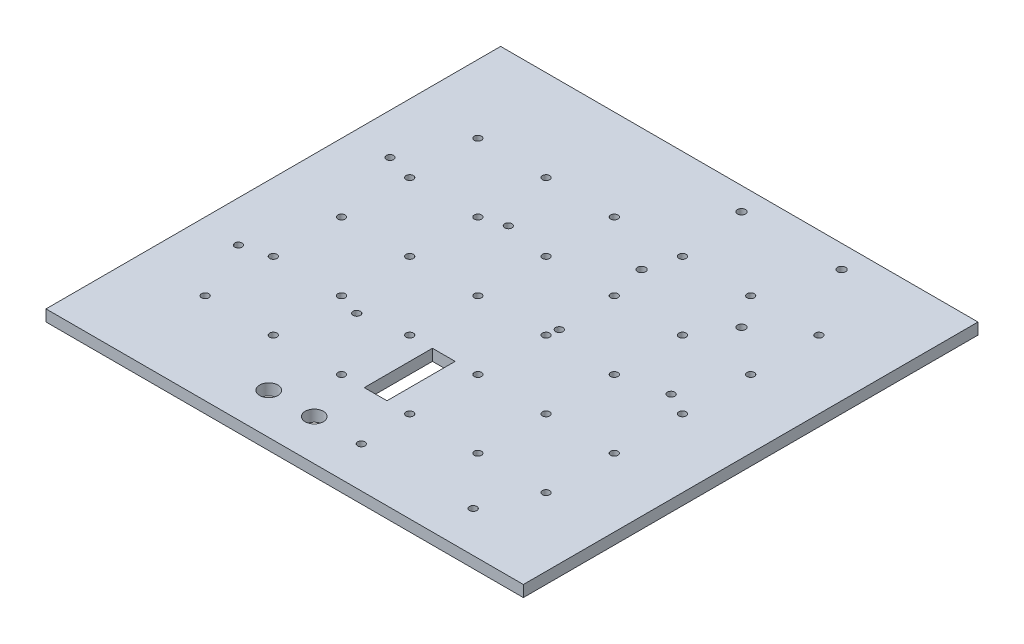
SolidWorks part; units mm, degrees
ref_plane "前视基准面" through (0, 0, 0) normal (0, 0, 1) x (1, 0, 0)
ref_plane "上视基准面" through (0, 0, 0) normal (0, 1, 0) x (1, 0, 0)
ref_plane "右视基准面" through (0, 0, 0) normal (1, 0, 0) x (0, 0, -1)
other "Configuration Table"
sketch "草图1" plane through (0, 0, 0) normal (0, 1, 0) x (1, 0, 0)
  line L4 (105.7144, 99.2856) -> (-104.2856, 99.2856)
  line L5 (-104.2856, 99.2856) -> (-104.2856, -100.7144)
  line L6 (-104.2856, -100.7144) -> (105.7144, -100.7144)
  line L7 (105.7144, -100.7144) -> (105.7144, 99.2856)
  circle A0 centre (-74.2856, -60.7144) radius 1.6
  circle A1 centre (75.7144, 59.2856) radius 1.6
  circle A2 centre (-74.2856, 29.2856) radius 1.6
  circle A3 centre (-74.2856, -0.7144) radius 1.6
  circle A4 centre (-74.2856, -30.7144) radius 1.6
  circle A5 centre (-44.2856, -60.7144) radius 1.6
  circle A6 centre (-44.2856, 59.2856) radius 1.6
  circle A7 centre (45.7144, 59.2856) radius 1.6
  circle A8 centre (75.7144, -30.7144) radius 1.6
  circle A9 centre (75.7144, -0.7144) radius 1.6
  circle A10 centre (45.7144, -60.7144) radius 1.6
  circle A11 centre (75.7144, 29.2856) radius 1.6
  circle A12 centre (75.7144, -60.7144) radius 1.6
  circle A13 centre (-74.2856, 59.2856) radius 1.6
  circle A14 centre (-44.2856, 29.2856) radius 1.6
  circle A15 centre (-44.2856, -0.7144) radius 1.6
  circle A16 centre (-44.2856, -30.7144) radius 1.6
  circle A17 centre (-14.2856, 59.2856) radius 1.6
  circle A21 centre (-14.2856, -60.7144) radius 1.6
  circle A22 centre (15.7144, 59.2856) radius 1.6
  circle A26 centre (15.7144, -60.7144) radius 1.6
  circle A27 centre (45.7144, 59.2856) radius 1.6
  circle A28 centre (45.7144, 29.2856) radius 1.6
  circle A29 centre (45.7144, -0.7144) radius 1.6
  circle A30 centre (45.7144, -30.7144) radius 1.6
  circle A31 centre (45.7144, -60.7144) radius 1.6
  circle A32 centre (15.7144, 29.2856) radius 1.6 [skipped]
  circle A33 centre (-14.2856, 29.2856) radius 1.6 [skipped]
  circle A34 centre (-14.2856, -0.7144) radius 1.6 [skipped]
  circle A35 centre (15.7144, -0.7144) radius 1.6 [skipped]
  circle A36 centre (15.7144, -30.7144) radius 1.6 [skipped]
  circle A37 centre (-14.2856, -30.7144) radius 1.6 [skipped]
  dimension "D1" = 210
  dimension "D2" = 4
  dimension "D3" = 4
extrude "凸台-拉伸1" add sketch "草图1" along normal blind 5
sketch "草图3" plane through (0, 5, 0) normal (0, 1, 0) x (1, 0, 0)
  line L0 (105.7144, -100.7144) -> (105.7144, 99.2856) construction
  line L1 (-86.2856, -34.0644) -> (-34.2356, -34.0644)
  line L2 (-86.2856, -34.0644) -> (-86.2856, 32.6356)
  line L3 (-86.2856, 32.6356) -> (-34.2356, 32.6356) construction
  line L4 (-34.2356, -34.0644) -> (-34.2356, 32.6356)
  line L5 (-86.2856, -34.0644) -> (-34.2356, 32.6356) construction
  line L6 (-86.2856, 32.6356) -> (-34.2356, -34.0644) construction
  line L7 (16.5044, -82.7944) -> (65.7144, -82.7944)
  line L8 (16.5044, -82.7944) -> (16.5044, 4.2856)
  line L9 (16.5044, 4.2856) -> (65.7144, 4.2856) construction
  line L10 (65.7144, -82.7944) -> (65.7144, 4.2856)
  line L11 (16.5044, -82.7944) -> (65.7144, 4.2856) construction
  line L12 (16.5044, 4.2856) -> (65.7144, -82.7944) construction
  line L13 (105.7144, 99.2856) -> (-104.2856, 99.2856) construction
  line L14 (-104.2856, 99.2856) -> (-104.2856, -100.7144) construction
  circle A1 centre (-34.2356, 32.6356) radius 1.6
  circle A2 centre (-86.2856, 32.6356) radius 1.6
  circle A3 centre (-86.2856, -34.0644) radius 1.6
  circle A4 centre (-34.2356, -34.0644) radius 1.6
  circle A5 centre (16.5044, 4.2856) radius 1.6
  circle A6 centre (65.7144, 4.2856) radius 1.6
  circle A7 centre (16.5044, -82.7944) radius 1.6
  circle A8 centre (65.7144, -82.7944) radius 1.6
  point P0 (-60.2606, -0.7144)
  point P6 (41.1094, -39.2544)
  dimension "D9" = 3.2
  dimension "D10" = 3.2
  dimension "D11" = 3.2
  dimension "D12" = 3.2
  dimension "D13" = 3.2
  dimension "D14" = 3.2
  dimension "D15" = 3.2
  dimension "D16" = 3.2
  dimension "D1" = 66.7
  dimension "D2" = 52.05
  dimension "D3" = 87.08
  dimension "D4" = 49.21
  dimension "D5" = 40
  dimension "D6" = 95
  dimension "D7" = 18
  dimension "D8" = 66.65
extrude "切除-拉伸1" cut sketch "草图3" against normal blind 5
sketch "草图4" plane through (0, 5, 0) normal (0, 1, 0) x (1, 0, 0)
  line L0 (105.7144, -100.7144) -> (105.7144, 99.2856) construction
  line L1 (-104.2856, -100.7144) -> (105.7144, -100.7144) construction
  circle A1 centre (65.7144, -82.7944) radius 1.6
  circle A2 centre (65.7144, -82.7944) radius 1.6
  circle A3 centre (-4.2856, -82.7144) radius 4
  circle A4 centre (-24.2856, -82.7144) radius 4
  dimension "D2" = 8
  dimension "D3" = 8
  dimension "D4" = 20
  dimension "D5" = 110
  dimension "D6" = 18
  dimension "D7" = 18
  dimension "D1" = 0
extrude "切除-拉伸2" cut sketch "草图4" against normal blind 5
sketch "草图5" plane through (0, 5, 0) normal (0, 1, 0) x (1, 0, 0)
  circle A0 centre (-14.2856, 59.2856) radius 1.6 construction
  circle A1 centre (-14.2856, 59.2856) radius 1.6
  circle A2 centre (15.7144, 59.2856) radius 1.6 construction
  circle A3 centre (15.7144, 59.2856) radius 1.6
  circle A4 centre (-14.2856, 29.2856) radius 1.6
  circle A5 centre (15.7144, 29.2856) radius 1.6
  circle A6 centre (-14.2856, -0.7144) radius 1.6
  circle A7 centre (15.7144, -0.7144) radius 1.6
  circle A8 centre (-14.2856, -30.7144) radius 1.6
  circle A9 centre (15.7144, -30.7144) radius 1.6
  dimension "D2" = 30
  dimension "D1" = 4
extrude "切除-拉伸3" cut sketch "草图5" against normal through all
sketch "草图6" plane through (0, 5, 0) normal (0, 1, 0) x (1, 0, 0)
  line L0 (105.7144, -100.7144) -> (105.7144, 99.2856) construction
  line L1 (-4.2856, -30.7144) -> (5.7144, -30.7144)
  line L2 (-4.2856, -30.7144) -> (-4.2856, -60.7144)
  line L3 (-4.2856, -60.7144) -> (5.7144, -60.7144)
  line L4 (5.7144, -30.7144) -> (5.7144, -60.7144)
  line L5 (-104.2856, -100.7144) -> (105.7144, -100.7144) construction
  dimension "D1" = 100
  dimension "D2" = 10
  dimension "D3" = 40
  dimension "D4" = 30
extrude "切除-拉伸4" cut sketch "草图6" against normal through all
sketch "草图7" plane through (0, 5, 0) normal (0, 1, 0) x (1, 0, 0)
  line L1 (11.7144, 89.2856) -> (55.7144, 89.2856)
  line L2 (11.7144, 89.2856) -> (11.7144, 45.2856)
  line L3 (11.7144, 45.2856) -> (55.7144, 45.2856)
  line L4 (-104.2856, -100.7144) -> (105.7144, -100.7144)
  line L5 (105.7144, -100.7144) -> (105.7144, 99.2856)
  line L6 (105.7144, 99.2856) -> (-104.2856, 99.2856)
  line L7 (-104.2856, 99.2856) -> (-104.2856, -100.7144)
  line L8 (-104.2856, -100.7144) -> (105.7144, -100.7144)
  line L9 (105.7144, -100.7144) -> (105.7144, 99.2856)
  line L10 (105.7144, 99.2856) -> (-104.2856, 99.2856)
  line L11 (-104.2856, 99.2856) -> (-104.2856, -100.7144)
  line L12 (55.7144, 89.2856) -> (55.7144, 45.2856)
  line L13 (11.7144, 89.2856) -> (55.7144, 45.2856) construction
  line L14 (11.7144, 45.2856) -> (55.7144, 89.2856) construction
  circle A0 centre (11.7144, 89.2856) radius 1.75
  circle A1 centre (55.7144, 89.2856) radius 1.75
  circle A2 centre (55.7144, 45.2856) radius 1.75
  circle A3 centre (11.7144, 45.2856) radius 1.75
  point P2 (33.7144, 67.2856)
  dimension "D6" = 3.5
  dimension "D7" = 3.5
  dimension "D8" = 3.5
  dimension "D9" = 3.5
  dimension "D2" = 44
  dimension "D3" = 44
  dimension "D4" = 50
  dimension "D5" = 10
  dimension "D1" = 0
extrude "切除-拉伸5" cut sketch "草图7" against normal through all contours L1 A0 L2 | L2 A0 L1 | L3 A3 L2 | L2 A3 L3 | L12 A2 L3 | L3 A2 L12 | L1 A1 L12 | L12 A1 L1
